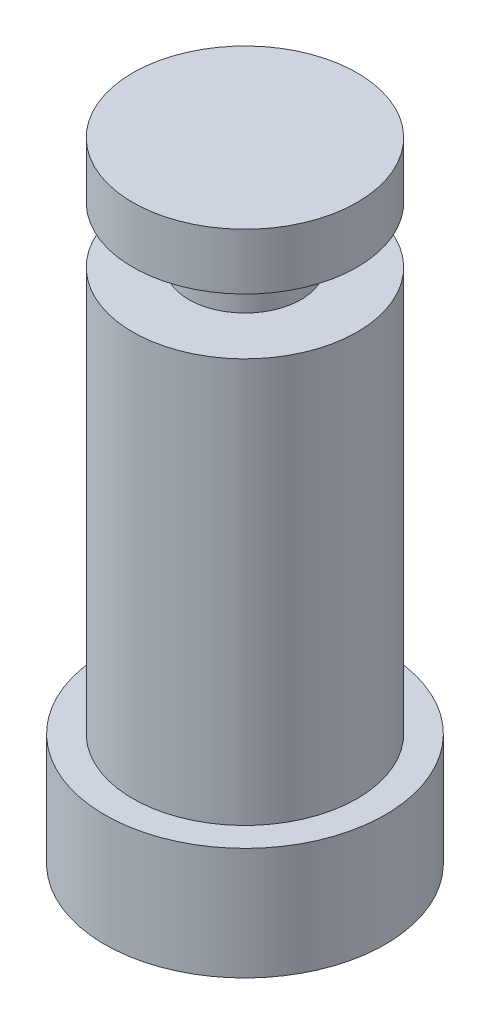
SolidWorks part; units mm, degrees
material "K110"
ref_plane "Front Plane" through (0, 0, 0) normal (0, 0, 1) x (1, 0, 0)
ref_plane "Top Plane" through (0, 0, 0) normal (0, 1, 0) x (1, 0, 0)
ref_plane "Right Plane" through (0, 0, 0) normal (1, 0, 0) x (0, 0, -1)
sketch "Sketch1" plane through (0, 0, 0) normal (0, 0, 1) x (1, 0, 0)
  line L0 (0, 0) -> (5, 0)
  line L1 (5, 0) -> (5, -23)
  line L2 (5, -23) -> (6.25, -23)
  line L3 (6.25, -23) -> (6.25, -28)
  line L4 (6.25, -28) -> (0, -28)
  line L5 (0, -28) -> (0, 0)
  line L6 (0, 5) -> (0, -33) construction
  point P9 (2.5, 0)
  dimension "D1" = 5
  dimension "D2" = 5
  dimension "D3" = 10
  dimension "D4" = 12.5
  dimension "D5" = 5
  dimension "D6" = 23
revolve "Revolve1" add sketch "Sketch1" angle 360 about L6
sketch "Sketch2" plane through (0, 0, 0) normal (0, 0, 1) x (1, 0, 0)
  line L0 (0, 0) -> (0, -28) construction
  line L1 (-6.25, -28) -> (6.25, -28) construction
  line L2 (5, -23) -> (5, 0) construction
  line L3 (5, -2.5) -> (2.5, -2.5)
  line L4 (5, -2.5) -> (5, -5)
  line L5 (5, -5) -> (2.5, -5)
  line L6 (2.5, -2.5) -> (2.5, -5)
  line L7 (6.25, -23) -> (-6.25, -23) construction
  dimension "D1" = 5
  dimension "D2" = 2.5
  dimension "D3" = 18
revolve "Cut-Revolve1" cut sketch "Sketch2" angle 360 about L0
